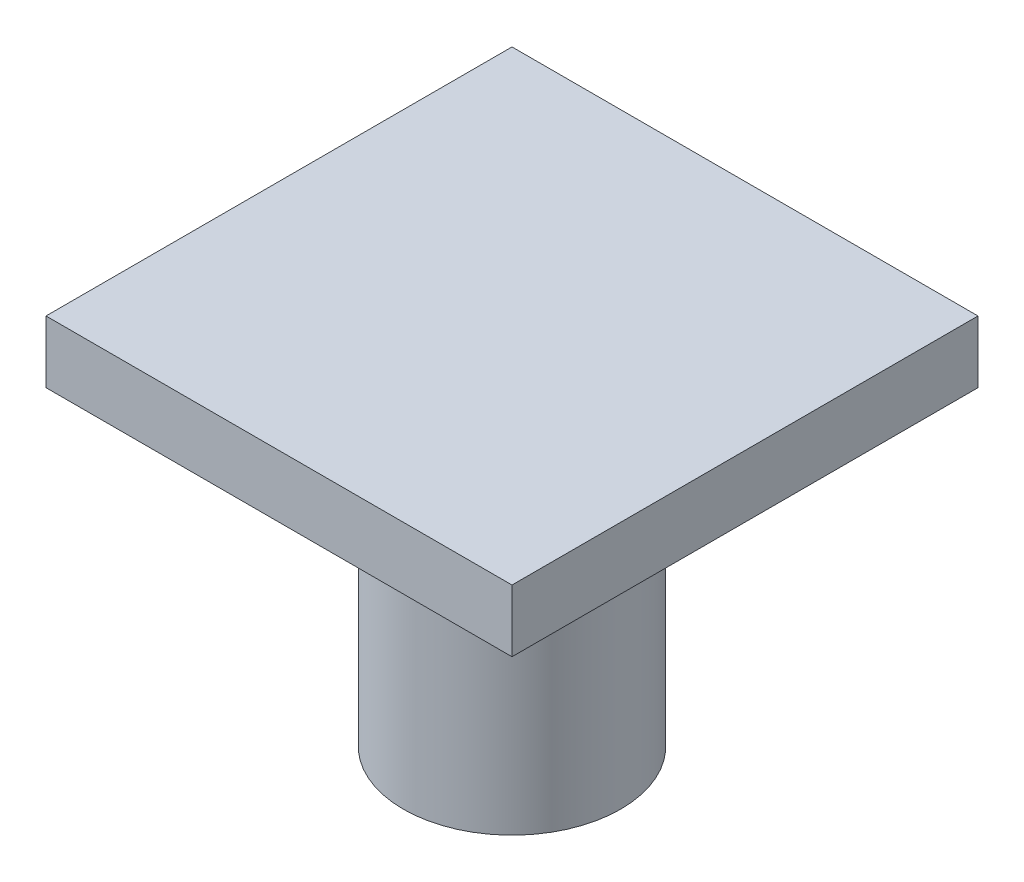
SolidWorks part; units mm, degrees
ref_plane "Front Plane" through (0, 0, 0) normal (0, 0, 1) x (1, 0, 0)
ref_plane "Top Plane" through (0, 0, 0) normal (0, 1, 0) x (1, 0, 0)
ref_plane "Right Plane" through (0, 0, 0) normal (1, 0, 0) x (0, 0, -1)
sketch "Sketch2" plane through (0, 0, 0) normal (0, 1, 0) x (1, 0, 0)
  line L1 (-7.5, -7.5) -> (7.5, -7.5)
  line L2 (-7.5, -7.5) -> (-7.5, 7.5)
  line L3 (-7.5, 7.5) -> (7.5, 7.5)
  line L4 (7.5, -7.5) -> (7.5, 7.5)
  line L5 (-7.5, -7.5) -> (7.5, 7.5) construction
  line L6 (-7.5, 7.5) -> (7.5, -7.5) construction
  point P0 (0, 0)
  dimension "D1" = 15
  dimension "D2" = 15
extrude "Boss-Extrude1" add sketch "Sketch2" along normal blind 2
sketch "Sketch3" plane through (0, 0, 0) normal (0, -1, 0) x (1, 0, 0)
  circle A0 centre (0, 0) radius 3.5
  circle A1 centre (0, 0) radius 2.5
  dimension "D1" = 7
  dimension "D2" = 5
extrude "Boss-Extrude2" add sketch "Sketch3" along normal blind 10
fillet "Fillet1" radius 1 1 edges at (0, 0, -3.5)
fillet "Fillet2" radius 1 1 edges at (0, 0, -2.5)
